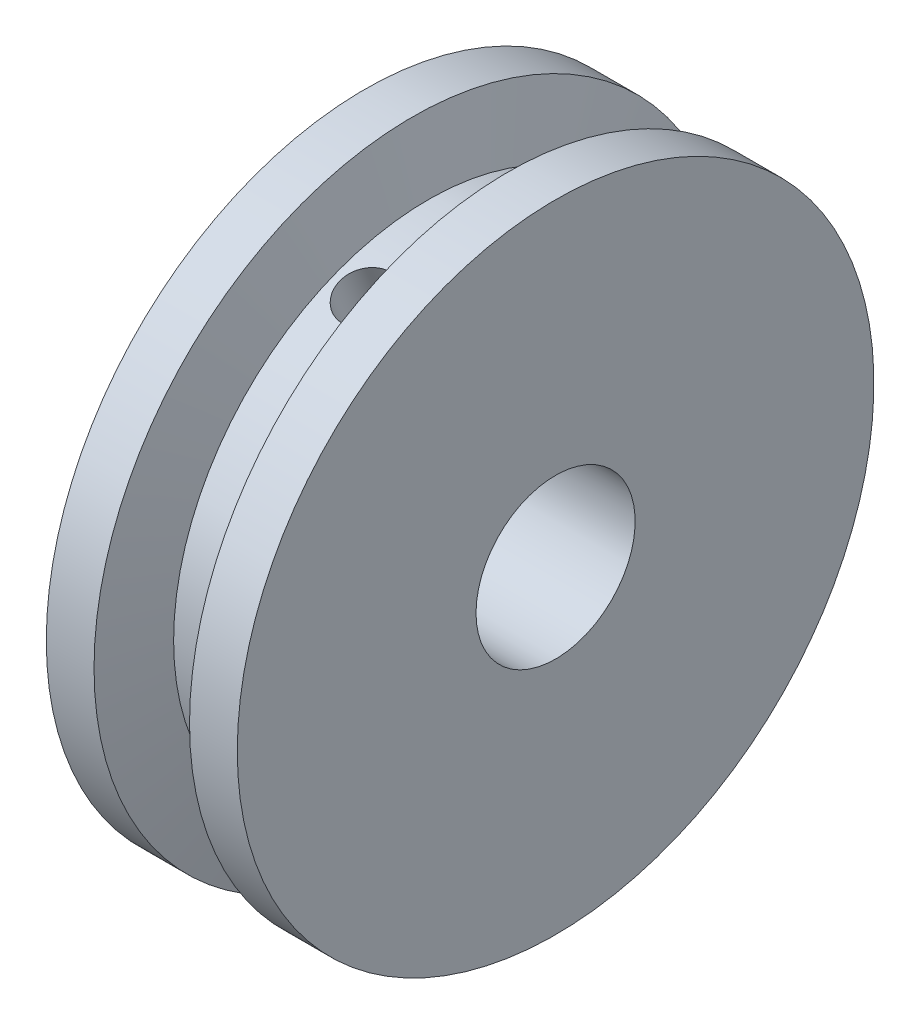
SolidWorks part; units mm, degrees
ref_plane "Front Plane" through (0, 0, 0) normal (0, 0, 1) x (1, 0, 0)
ref_plane "Top Plane" through (0, 0, 0) normal (0, 1, 0) x (1, 0, 0)
ref_plane "Right Plane" through (0, 0, 0) normal (1, 0, 0) x (0, 0, -1)
sketch "Sketch1" plane through (0, 0, 0) normal (0, 0, 1) x (1, 0, 0)
  line L1 (-2, 1.741) -> (2, 1.741)
  line L2 (2, 1.741) -> (3, 5.741)
  line L3 (3, 5.741) -> (6, 5.741)
  line L4 (6, 5.741) -> (6, -9.259)
  line L5 (6, -9.259) -> (-6, -9.259)
  line L7 (-2, 1.741) -> (-3, 5.741)
  line L8 (-6, 5.741) -> (-6, -9.259)
  line L9 (-3, 5.741) -> (-6, 5.741)
  line L10 (-24.2895, -14.259) -> (25.6345, -14.259) construction
  dimension "D2" = 3
  dimension "D3" = 15
  dimension "D5" = 4
  dimension "D6" = 5
revolve "Revolve1" add sketch "Sketch1" angle 360 about L10
hole_wizard "M4x0.7 Tapped Hole1" positions "3DSketch3" profile "Sketch5" tap size "M4x0.7" standard "ANSI Metric"
sketch3d "3DSketch3"
  point P0 (0, 0, 0)
  point P3 (0.113, 0.5565, 6.0416)
sketch "Sketch5" plane through (0.113, 0.5565, 6.0416) normal (1, 0, 0) x (0, -0.3776, 0.926)
  line L0 (0, 0) -> (0, 12)
  line L1 (0, 12) -> (1.65, 12)
  line L2 (1.65, 12) -> (1.65, 0)
  line L5 (1.65, 0) -> (0, 0)
  line L10 (0, 12) -> (-1.65, 12) construction
  line L11 (0, -6.35) -> (0, 107.95) construction
  dimension "Tap Drill Dia." = 3.3
  dimension "Tap Drill Depth" = 12
  dimension "Drill Angle" = 180
cosmetic thread "Hole Thread1" parameters "D1"=11.2801, "D2"=4
